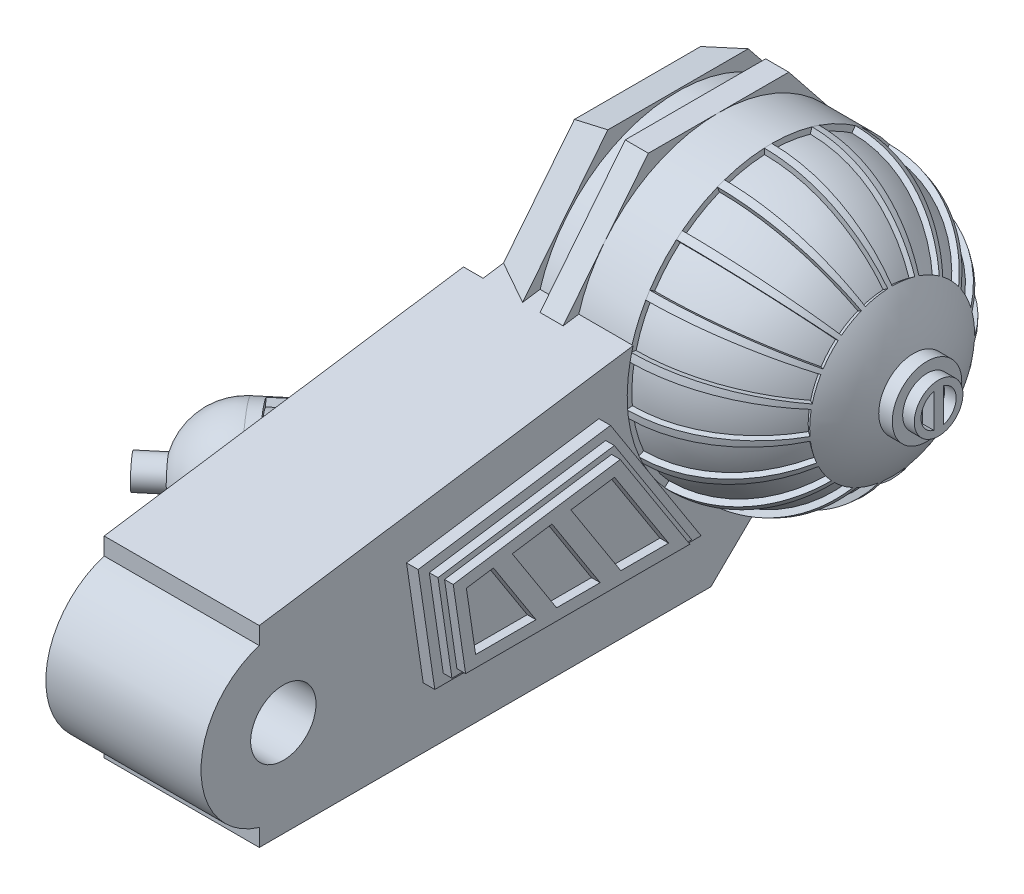
SolidWorks part; units mm, degrees
ref_plane "Front Plane" through (0, 0, 0) normal (0, 0, 1) x (1, 0, 0)
ref_plane "Top Plane" through (0, 0, 0) normal (0, 1, 0) x (1, 0, 0)
ref_plane "Right Plane" through (0, 0, 0) normal (1, 0, 0) x (0, 0, -1)
sketch "Sketch1" plane through (0, 0, 0) normal (1, 0, 0) x (0, 0, -1)
  line L0 (0, 0) -> (0, 12.592) construction
  line L1 (6.064, 12.592) -> (-6.064, 12.592)
  line L2 (-6.064, 12.592) -> (-13.6257, 3.11)
  line L3 (-13.6257, 3.11) -> (-10.927, -8.714)
  line L4 (-10.927, -8.714) -> (0, -13.9761)
  line L5 (0, -13.9761) -> (10.927, -8.714)
  line L6 (10.927, -8.714) -> (13.6257, 3.11)
  line L7 (13.6257, 3.11) -> (6.064, 12.592)
  circle A0 centre (0, 0) radius 12.592 construction
extrude "LegBase" add sketch "Sketch1" along normal blind 2
sketch "Sketch2" plane through (2, 0, 0) normal (1, 0, 0) x (0, 0, -1)
  line L0 (0, 0) -> (0, 12.592) construction
  line L1 (6.064, 12.592) -> (-6.064, 12.592) construction
  circle A0 centre (0, 0) radius 12.592
extrude "Boss-Extrude2" add sketch "Sketch2" along normal blind 4.6
sketch "Sketch3" plane through (6.6, 0, 0) normal (1, 0, 0) x (0, 0, -1)
  line L0 (0, 12.592) -> (0, -12.592)
  circle A0 centre (0, 0) radius 12.592 construction
  arc A1 (0, 12.592) -> (0, -12.592) centre (0, 0) cw
revolve "Revolve1" add sketch "Sketch3" angle 180 about L0
sketch "Sketch4" plane through (0, 0, 0) normal (1, 0, 0) x (0, 0, -1)
  circle A0 centre (0, 0) radius 3
extrude "Boss-Extrude3" add sketch "Sketch4" along normal blind 20
sketch "Sketch5" plane through (20, 0, 0) normal (1, 0, 0) x (0, 0, -1)
  circle A0 centre (0, 0) radius 2.1
extrude "Boss-Extrude4" add sketch "Sketch5" along normal blind 1
sketch "Sketch6" plane through (21, 0, 0) normal (1, 0, 0) x (0, 0, -1)
  line L1 (0.4096, -1.5195) -> (-0.4096, -1.5195)
  line L2 (0.4096, -1.5195) -> (0.4096, 1.5195)
  line L3 (0.4096, 1.5195) -> (-0.4096, 1.5195)
  line L4 (-0.4096, -1.5195) -> (-0.4096, 1.5195)
  line L5 (0.4096, -1.5195) -> (-0.4096, 1.5195) construction
  line L6 (0.4096, 1.5195) -> (-0.4096, -1.5195) construction
  circle A0 centre (0, 0) radius 1.5195
  dimension "D1" = 3.039
extrude "Cut-Extrude1" cut sketch "Sketch6" against normal blind 1 contours L4 A0 | L2 A0
sketch "Sketch8" plane through (0, 0, 0) normal (-1, 0, 0) x (0, 0, 1)
  circle A0 centre (0, 0) radius 12.4439
extrude "Boss-Extrude5" add sketch "Sketch8" along normal blind 1.5
sketch "Sketch11" plane through (-1.5, 0, 0) normal (-1, 0, 0) x (0, 0, 1)
  line L1 (-6.064, 12.592) -> (-13.6257, 3.11)
  line L2 (-13.6257, 3.11) -> (-10.927, -8.714)
  line L3 (-10.927, -8.714) -> (0, -13.9761)
  line L4 (0, -13.9761) -> (10.927, -8.714)
  line L5 (10.927, -8.714) -> (13.6257, 3.11)
  line L6 (13.6257, 3.11) -> (6.064, 12.592)
  line L7 (6.064, 12.592) -> (-6.064, 12.592)
  circle A0 centre (0, 0) radius 12.592 construction
extrude "Boss-Extrude6" add sketch "Sketch11" along normal blind 3.5
draft "Draft6" type of draft neutral plane draft angle 20 faces to draft 7 face at (-3.25, -2.802, 12.2763) face at (-3.25, 7.851, 9.8449) face at (-3.25, 12.592, 0) face at (-3.25, 7.851, -9.8449) face at (-3.25, -2.802, -12.2763) face at (-3.25, -11.345, -5.4635) face at (-3.25, -11.345, 5.4635) neutral plane through (-1.5, 0, 0) neutral plane normal (1, 0, 0) reverse direction yes parameters "D1"=20
sketch "Sketch12" plane through (0, 0, 0) normal (1, 0, 0) x (0, 0, -1)
  line L0 (0, 0) -> (0, 5.3563)
  line L1 (0, 5.3563) -> (-44.3644, -1.2335)
  line L2 (-44.3644, -1.2335) -> (-44.3644, -17.8335)
  line L3 (-44.3644, -17.8335) -> (-5.3644, -17.8335)
  line L4 (-5.3644, -17.8335) -> (0, -12.592)
  line L5 (0, -12.592) -> (0, 0)
  arc A1 (-5.4635, -11.345) -> (5.4635, -11.345) centre (0, 0) ccw construction
  dimension "D1" = 7.5
  dimension "D2" = 39
  dimension "D3" = 16.6
extrude "LowerThigh" add sketch "Sketch12" along normal blind 6.7 and the other way up to surface other way up to face at (-5, 0, 0)
sketch "Sketch13" plane through (6.7, 0, 0) normal (1, 0, 0) x (0, 0, -1)
  line L0 (-31.6507, -2.8984) -> (-15.033, -0.43)
  line L1 (-15.033, -0.43) -> (-7.2108, -12.592)
  line L2 (-7.2108, -12.592) -> (-30.2108, -12.592)
  line L3 (-30.2108, -12.592) -> (-31.6507, -2.8984)
  line L5 (0, -12.592) -> (0, -12.5916)
  line L6 (-12.0772, 3.5624) -> (-44.3644, -1.2335)
  line L7 (-44.3644, -1.2335) -> (-44.3644, -17.8335)
  line L8 (-44.3644, -17.8335) -> (-5.3644, -17.8335)
  line L9 (-5.3644, -17.8335) -> (0, -12.592)
  line L10 (0, -12.592) -> (0, -12.5916) construction
  line L11 (-12.0772, 3.5624) -> (-44.3644, -1.2335) construction
  line L12 (-44.3644, -1.2335) -> (-44.3644, -17.8335) construction
  line L13 (-44.3644, -17.8335) -> (-5.3644, -17.8335) construction
  line L14 (-5.3644, -17.8335) -> (0, -12.592) construction
  arc A1 (-12.0772, 3.5624) -> (0, -12.5916) centre (0, 0) ccw
  arc A2 (-12.0772, 3.5624) -> (0, -12.5916) centre (0, 0) ccw construction
  dimension "D2" = 23
  dimension "D3" = 9.8
  dimension "D4" = 16.8
  dimension "D1" = 0
extrude "Boss-Extrude8" add sketch "Sketch13" along normal blind 1
sketch "Sketch14" plane through (7.7, 0, 0) normal (1, 0, 0) x (0, 0, -1)
  line L8 (-30.6851, -3.6143) -> (-29.4778, -11.742)
  line L9 (-29.4778, -11.742) -> (-8.7682, -11.742)
  line L10 (-8.7682, -11.742) -> (-15.451, -1.3515)
  line L11 (-15.451, -1.3515) -> (-30.6851, -3.6143)
  line L12 (-30.6851, -3.6143) -> (-29.4778, -11.742)
  line L13 (-29.4778, -11.742) -> (-8.7682, -11.742)
  line L14 (-8.7682, -11.742) -> (-15.451, -1.3515)
  line L15 (-15.451, -1.3515) -> (-30.6851, -3.6143)
  dimension "D1" = 0.85
extrude "Boss-Extrude9" add sketch "Sketch14" along normal blind 0.75
sketch "Sketch15" plane through (8.45, 0, 0) normal (1, 0, 0) x (0, 0, -1)
  line L0 (-26.6464, -4.5309) -> (-28.9809, -4.8776)
  line L1 (-16.1887, -2.9775) -> (-28.9809, -4.8776) construction
  line L2 (-21.5839, -3.7789) -> (-25.0178, -4.2889)
  line L3 (-15.6428, -10.242) -> (-11.5164, -10.242)
  line L4 (-16.1887, -2.9775) -> (-19.9553, -3.537)
  line L5 (-28.9809, -4.8776) -> (-28.1841, -10.242)
  line L6 (-28.1841, -10.242) -> (-22.9732, -10.242)
  line L7 (-11.5164, -10.242) -> (-16.1887, -2.9775)
  line L8 (-15.6969, -1.8935) -> (-30.117, -4.0354)
  line L9 (-30.117, -4.0354) -> (-29.0466, -11.242)
  line L10 (-29.0466, -11.242) -> (-9.6842, -11.242)
  line L11 (-9.6842, -11.242) -> (-15.6969, -1.8935)
  line L12 (-15.6969, -1.8935) -> (-30.117, -4.0354)
  line L13 (-30.117, -4.0354) -> (-29.0466, -11.242)
  line L14 (-29.0466, -11.242) -> (-9.6842, -11.242)
  line L15 (-9.6842, -11.242) -> (-15.6969, -1.8935)
  line L16 (-26.6464, -4.5309) -> (-22.9732, -10.242)
  line L17 (-25.0178, -4.2889) -> (-21.189, -10.242)
  line L18 (-21.5839, -3.7789) -> (-17.427, -10.242)
  line L19 (-19.9553, -3.537) -> (-15.6428, -10.242)
  line L20 (-24.3655, -8.0772) -> (-23.1034, -7.2655) construction
  line L21 (-19.1391, -7.58) -> (-17.877, -6.7683) construction
  line L22 (-28.1841, -10.242) -> (-11.5164, -10.242) construction
  line L23 (-21.189, -10.242) -> (-17.427, -10.242)
  dimension "D1" = 0.5
  dimension "D2" = 1
extrude "Boss-Extrude10" add sketch "Sketch15" along normal blind 0.75
sketch "Sketch16" plane through (-5, 0, 0) normal (-1, 0, 0) x (0, 0, 1)
  line L0 (13.3346, 3.3756) -> (1.1091, -13.6757)
  line L1 (5.3644, -17.8335) -> (0, -12.592) construction
  line L10 (-9.8215, -7.8324) -> (0, -12.5622)
  line L11 (0, -12.5622) -> (0, -12.592)
  line L12 (0, -12.592) -> (5.3644, -17.8335)
  line L13 (5.3644, -17.8335) -> (44.3644, -17.8335)
  line L14 (44.3644, -17.8335) -> (44.3644, -1.2335)
  line L15 (44.3644, -1.2335) -> (11.5762, 3.6368)
  line L16 (11.5762, 3.6368) -> (5.4505, 11.3182)
  line L17 (5.4505, 11.3182) -> (-5.4505, 11.3182)
  line L18 (-5.4505, 11.3182) -> (-12.2472, 2.7954)
  line L19 (-12.2472, 2.7954) -> (-9.8215, -7.8324)
  line L22 (1.1091, -13.6757) -> (5.3644, -17.8335)
  line L23 (5.3644, -17.8335) -> (44.3644, -17.8335)
  line L24 (44.3644, -17.8335) -> (44.3644, -1.2335)
  line L25 (44.3644, -1.2335) -> (13.3346, 3.3756)
  dimension "D1" = 0
extrude "Boss-Extrude11" add sketch "Sketch16" along normal blind 1.7
sketch "Sketch17" plane through (6.7, 0, 0) normal (1, 0, 0) x (0, 0, -1)
  line L0 (-44.3644, -17.8335) -> (-44.3644, -16.3335) construction
  line L1 (-44.3644, -1.2335) -> (-44.3644, -17.8335) construction
  line L2 (-44.3644, -1.2335) -> (-44.3644, -2.7335) construction
  line L3 (-44.3644, -2.7335) -> (-44.3644, -16.3335)
  arc A0 (-44.3644, -2.7335) -> (-44.3644, -16.3335) centre (-42.2904, -9.5335) ccw
  dimension "D1" = 1.5
extrude "EndJoint" add sketch "Sketch17" against normal up to surface (13.4 mm away) up to face at (-6.7, -9.4401, 21.7074)
sketch "Sketch18" plane through (6.7, 0, 0) normal (1, 0, 0) x (0, 0, -1)
  circle A0 centre (-42.2904, -9.5335) radius 2.8205
extrude "Cut-Extrude2" cut sketch "Sketch18" against normal through all
sketch "Sketch19" plane through (-6.7, 0, 0) normal (-1, 0, 0) x (0, 0, 1)
  line L6 (-52.2394, 8.5665) -> (-52.2394, -13.3335)
  line L7 (36.3254, -4.5887) -> (36.3254, -13.3335)
  line L8 (7.8007, -12.0656) -> (9.0983, -13.3335)
  line L9 (1.1091, -13.6757) -> (5.3644, -17.8335) construction
  line L12 (39.8644, -5.1144) -> (15.3909, -1.4792)
  line L13 (15.3909, -1.4792) -> (7.0178, -13.1575)
  line L14 (7.0178, -13.1575) -> (7.1979, -13.3335)
  line L15 (7.1979, -13.3335) -> (39.8644, -13.3335)
  line L16 (39.8644, -13.3335) -> (39.8644, -10.4941)
  line L17 (39.8644, -8.5729) -> (39.8644, -5.1144)
  line L18 (36.3254, -4.5887) -> (15.3909, -1.4792)
  line L19 (15.3909, -1.4792) -> (7.8007, -12.0656)
  line L21 (9.0983, -13.3335) -> (36.3254, -13.3335)
  arc A2 (39.8644, -10.4941) -> (39.8644, -8.5729) centre (42.2904, -9.5335) ccw
  dimension "D1" = 4.5
extrude "Boss-Extrude13" add sketch "Sketch19" along normal blind 1 contours L8 L21 L7 L18 L19
sketch "TankLocation" plane through (-7.7, 0, 0) normal (-1, 0, 0) x (0, 0, 1)
  line L0 (36.3254, -4.5887) -> (36.3254, -13.3335) construction
  line L1 (30.3254, -6.376) -> (23.7691, -6.376)
  line L2 (30.3254, -6.376) -> (30.3254, -10.6205)
  line L3 (30.3254, -10.6205) -> (23.7691, -10.6205)
  line L4 (23.7691, -6.376) -> (23.7691, -10.6205)
  dimension "D1" = 6
ref_plane "TankPlane" through (-19.4509, 0, 16.3212) normal (0.766, 0, -0.6428) x (0, -1, 0)
sketch "Sketch21" plane through (-19.4509, 0, 16.3212) normal (0.766, 0, -0.6428) x (0, -1, 0)
  circle A0 centre (8.1556, -12.9502) radius 4.9751
extrude "Boss-Extrude14" add sketch "Sketch21" against normal blind 1 separate body
sketch "Sketch23" plane through (-19.4509, 0, 16.3212) normal (0.766, 0, -0.6428) x (-0.6428, 0, -0.766)
  circle A0 centre (-12.9502, -8.1556) radius 4.3768
extrude "Boss-Extrude15" add sketch "Sketch23" along normal up to next
sketch "Sketch24" plane through (-20.2169, 0, 16.964) normal (-0.766, 0, 0.6428) x (0.6428, 0, 0.766)
  line L0 (12.9502, -8.1556) -> (7.975, -8.1556) construction
  line L1 (12.9502, -8.1556) -> (8.0025, -8.6774)
  line L2 (12.9502, -8.1556) -> (8.0025, -7.6337)
  line L3 (8.0025, -7.6337) -> (7.975, -8.1556) construction
  line L4 (7.975, -8.1556) -> (8.0025, -8.6774) construction
  circle A1 centre (12.9502, -8.1556) radius 4.9751
  arc A2 (8.0025, -7.6337) -> (8.0025, -8.6774) centre (12.9502, -8.1556) ccw
  dimension "D1" = 0
extrude "Boss-Extrude16" add sketch "Sketch24" against normal up to surface (8.1016 mm away)
pattern_circular "CirPattern1" count 2 every 57 about axis through (8.3242, -8.1556, 9.9204) along (-0.766, 0, 0.6428) of "Boss-Extrude16"
pattern_circular "CirPattern2" count 2 every 57 about axis through (8.3242, -8.1556, 9.9204) along (0.766, 0, -0.6428) of "Boss-Extrude16"
sketch "Sketch28" plane through (-20.2169, 0, 16.964) normal (-0.766, 0, 0.6428) x (0.6428, 0, 0.766)
  circle A0 centre (12.9502, -8.1556) radius 1.3
extrude "Boss-Extrude18" add sketch "Sketch28" along normal blind 7
sketch "Sketch29" plane through (-20.2169, 0, 16.964) normal (-0.766, 0, 0.6428) x (0.6428, 0, 0.766)
  line L0 (12.9502, -3.1804) -> (12.9502, -13.1307)
  circle A0 centre (12.9502, -8.1556) radius 4.9751 construction
  arc A1 (12.9502, -13.1307) -> (12.9502, -3.1804) centre (12.9502, -8.1556) ccw
revolve "Revolve3" add sketch "Sketch29" angle 180 about L0
sketch "Sketch30" plane through (-7.7, 0, 0) normal (-1, 0, 0) x (0, 0, 1)
  ellipse E0 centre (23.8769, -8.1556) end of major axis (16.8717, -8.1556) minor radius 5.1216
  ellipse E1 centre (23.3663, -8.1556) end of major axis (29.8609, -8.1556) minor radius 4.9751 (16.9075, -7.6337) -> (16.9075, -8.6774) ccw construction
extrude "Boss-Extrude19" add sketch "Sketch30" along normal blind 0.5
sketch "Sketch32" plane through (0, 0, 0) normal (0, 0, 1) x (1, 0, 0)
  line L0 (16.9861, 7.1196) -> (16.5737, 6.8369)
  line L1 (6.6, 12.592) -> (6.6, 12.092)
  arc A0 (18.8295, 3) -> (6.6, 12.592) centre (6.6, 0) ccw construction
  arc A1 (16.9861, 7.1196) -> (6.6, 12.592) centre (6.6, 0) ccw
  arc A2 (16.5737, 6.8369) -> (6.6, 12.092) centre (6.6, 0) ccw
  dimension "D1" = 0.5
sketch "RotationAxis" plane through (0, 0, 0) normal (0, 0, 1) x (1, 0, 0)
  line L0 (0, 0) -> (16.6782, 0) construction
revolve "Cut-Revolve1" cut sketch "Sketch32" angle 360 about L0
sketch "Sketch34" plane through (0, 0, 0) normal (0, 0, 1) x (1, 0, 0)
  line L0 (6.6, 12.592) -> (6.6, 12.092)
  line L1 (16.5737, 6.8369) -> (16.9861, 7.1196)
  arc A1 (16.5737, 6.8369) -> (6.6, 12.092) centre (6.6, 0) ccw construction
  arc A2 (16.9861, 7.1196) -> (6.6, 12.592) centre (6.6, 0) ccw
  arc A3 (16.5737, 6.8369) -> (6.6, 12.092) centre (6.6, 0) ccw
revolve "Revolve4" add sketch "Sketch34" angle 3 about L0
pattern_circular "CirPattern5" count 19 over 360 about axis through (0, 0, 0) along (1, 0, 0) of "Revolve4"
